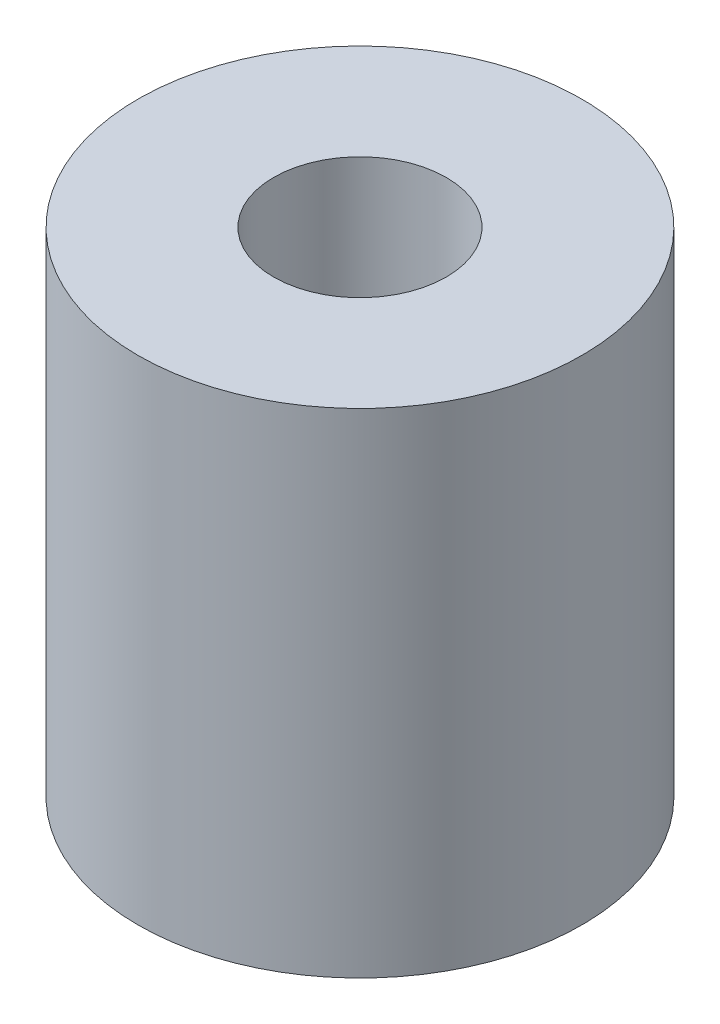
SolidWorks part; units mm, degrees
ref_plane "前视基准面" through (0, 0, 0) normal (0, 0, 1) x (1, 0, 0)
ref_plane "上视基准面" through (0, 0, 0) normal (0, 1, 0) x (1, 0, 0)
ref_plane "右视基准面" through (0, 0, 0) normal (1, 0, 0) x (0, 0, -1)
other "Configuration Table"
sketch "草图2" plane through (0, 0, 0) normal (0, 1, 0) x (1, 0, 0)
  circle A18 centre (0, 0) radius 4.5
  circle A19 centre (0, 0) radius 1.75
  dimension "D1" = 3.5
  dimension "D2" = 9
extrude "凸台-拉伸1" add sketch "草图2" along normal blind 10
